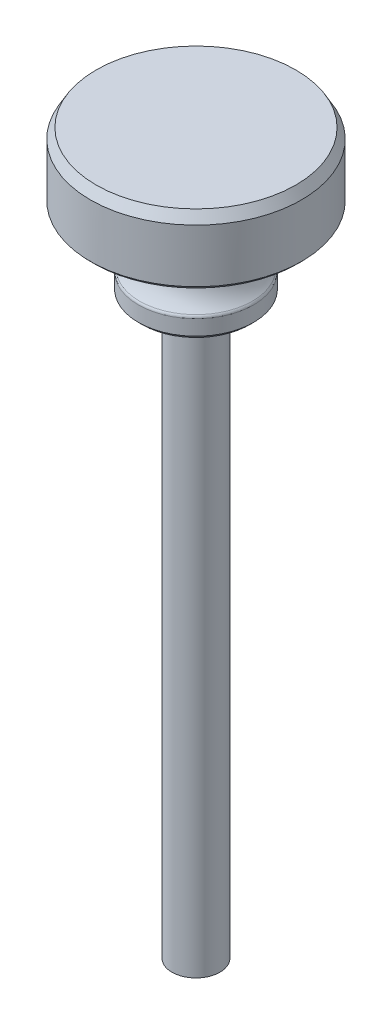
SolidWorks part; units mm, degrees
ref_plane "Front Plane" through (0, 0, 0) normal (0, 0, 1) x (1, 0, 0)
ref_plane "Top Plane" through (0, 0, 0) normal (0, 1, 0) x (1, 0, 0)
ref_plane "Right Plane" through (0, 0, 0) normal (1, 0, 0) x (0, 0, -1)
sketch "Sketch1" plane through (0, 0, 0) normal (0, 0, 1) x (1, 0, 0)
  line L0 (0, 0) -> (0, 101.2862) construction
  line L1 (0, -198.7138) -> (12.5, -198.7138)
  line L2 (12.5, -198.7138) -> (12.5, 101.2862)
  line L3 (12.5, 101.2862) -> (0, 101.2862)
  line L4 (0, 101.2862) -> (0, -198.7138)
  dimension "D1" = 25
  dimension "D2" = 300
revolve "Revolve1" add sketch "Sketch1" angle 360 about L0
sketch "Sketch2" plane through (0, 0, 0) normal (0, 0, 1) x (1, 0, 0)
  line L0 (12.5, 101.2862) -> (-12.5, 101.2862) construction
  line L1 (12.5, 101.2862) -> (0, 101.2862)
  line L2 (0, 176.2862) -> (0, 101.2862)
  line L3 (0, 101.2862) -> (30, 101.2862)
  line L4 (30, 101.2862) -> (30, 112.0444)
  line L6 (30, 141.2862) -> (55, 141.2862)
  line L7 (55, 141.2862) -> (55, 176.2862)
  line L8 (55, 176.2862) -> (0, 176.2862)
  line L10 (0, 0) -> (0, 53.8934) construction
  arc A1 (30, 141.2862) -> (30, 112.0444) centre (43.3667, 126.6653) ccw
  dimension "D2" = 75
  dimension "D3" = 35
revolve "Revolve2" add sketch "Sketch2" angle 360 about L10
chamfer "Chamfer1" distance 3 angle 60 1 edges at (0, 176.2862, -55)
chamfer "Chamfer2" distance 2 angle 45 1 edges at (0, 141.2862, -55)
chamfer "Chamfer3" distance 2 angle 45 1 edges at (0, 101.2862, -30)
fillet "Fillet1" radius 2 1 edges at (0, 112.0444, -30)
fillet "Fillet2" radius 2 1 edges at (0, 141.2862, -30)
scale "Scale1" scale about centroid uniform scaling yes scale factor 0.1
